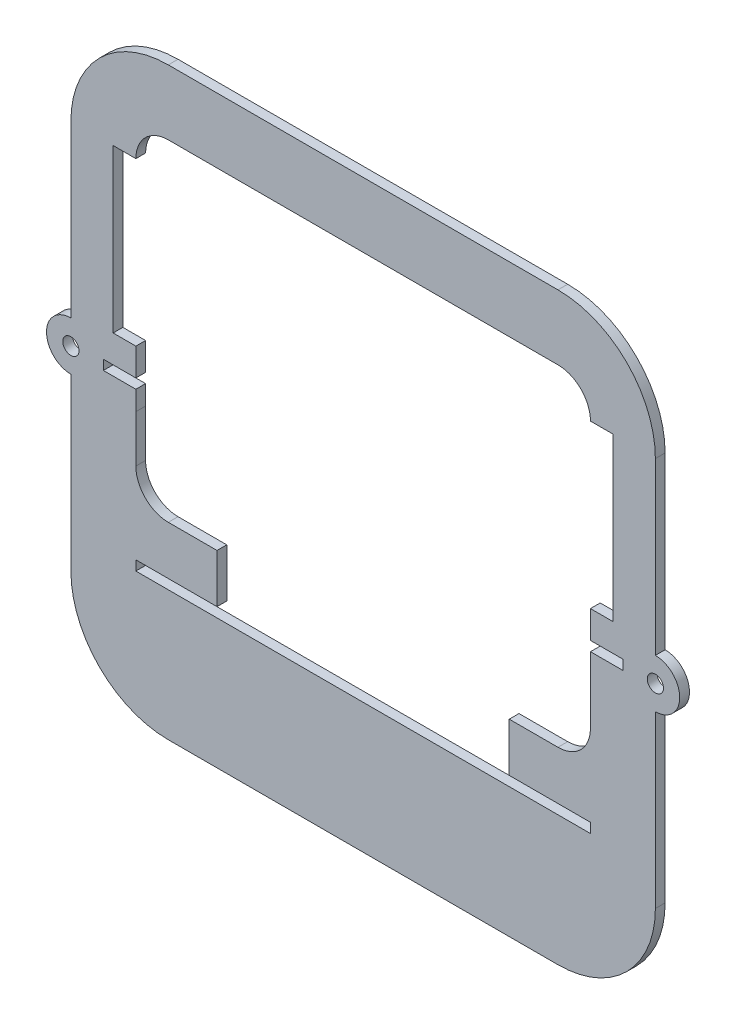
SolidWorks part; units mm, degrees
material "Teak"
ref_plane "Front Plane" through (0, 0, 0) normal (0, 0, 1) x (1, 0, 0)
ref_plane "Top Plane" through (0, 0, 0) normal (0, 1, 0) x (1, 0, 0)
ref_plane "Right Plane" through (0, 0, 0) normal (1, 0, 0) x (0, 0, -1)
sketch "Sketch1" plane through (0, 0, 0) normal (0, 0, 1) x (1, 0, 0)
  line L33 (167.7762, -174.9603) -> (287.7762, -174.9603)
  line L38 (317.7762, -144.9603) -> (317.7762, -92.4603)
  line L41 (226.2847, -14.9603) -> (167.7847, -14.9603)
  line L44 (229.2847, -14.9603) -> (226.2847, -14.9603)
  line L47 (287.7847, -14.9603) -> (229.2847, -14.9603)
  line L48 (304.7847, -24.9603) -> (297.7847, -24.9603)
  line L49 (304.7847, -74.9603) -> (304.7847, -24.9603)
  line L50 (297.7847, -74.9603) -> (304.7847, -74.9603)
  line L51 (297.7847, -83.4603) -> (297.7847, -74.9603)
  line L52 (307.7847, -83.4603) -> (297.7847, -83.4603)
  line L53 (307.7847, -86.4603) -> (307.7847, -83.4603)
  line L54 (297.7847, -86.4603) -> (307.7847, -86.4603)
  line L59 (157.7847, -74.9603) -> (157.7847, -83.4603)
  line L60 (150.7847, -74.9603) -> (157.7847, -74.9603)
  line L61 (150.7847, -24.9603) -> (150.7847, -74.9603)
  line L62 (157.7847, -24.9603) -> (150.7847, -24.9603)
  line L63 (287.7762, 5.0397) -> (167.7762, 5.0397)
  line L64 (137.7762, -24.9603) -> (137.7762, -77.4603)
  line L70 (147.7847, -86.4603) -> (147.7847, -83.4603)
  line L71 (157.7847, -86.4603) -> (147.7847, -86.4603)
  line L72 (147.7847, -83.4603) -> (157.7847, -83.4603)
  line L97 (137.7762, -92.4603) -> (137.7762, -144.9603)
  line L98 (317.7762, -77.4603) -> (317.7762, -24.9603)
  line L109 (297.7762, -134.9603) -> (297.7762, -131.9603)
  line L110 (157.7847, -86.4603) -> (157.7762, -92.4603)
  line L111 (297.7847, -86.4603) -> (297.7762, -92.4603)
  line L112 (157.7762, -134.9603) -> (297.7762, -134.9603)
  line L113 (157.7762, -92.4603) -> (157.7762, -144.9603) construction
  line L114 (167.7762, -154.9603) -> (287.7762, -154.9603) construction
  line L115 (297.7762, -144.9603) -> (297.7762, -92.4603) construction
  line L116 (297.7762, -106.9603) -> (297.7762, -92.4603)
  line L117 (287.7762, -116.9603) -> (272.7762, -116.9603)
  line L119 (297.7762, -131.9603) -> (272.7762, -131.9603)
  line L120 (272.7762, -116.9603) -> (272.7762, -131.9603)
  line L122 (157.7762, -106.9603) -> (157.7762, -92.4603)
  line L123 (157.7762, -134.9603) -> (157.7762, -131.9603)
  line L124 (157.7762, -131.9603) -> (182.7762, -131.9603)
  line L125 (167.7762, -116.9603) -> (182.7762, -116.9603)
  line L126 (182.7762, -116.9603) -> (182.7762, -131.9603)
  arc A22 (167.7847, -14.9603) -> (157.7847, -24.9603) centre (167.7847, -24.9603) ccw
  arc A23 (297.7847, -24.9603) -> (287.7847, -14.9603) centre (287.7847, -24.9603) ccw
  arc A26 (137.7762, -144.9603) -> (167.7762, -174.9603) centre (167.7762, -144.9603) ccw
  arc A27 (287.7762, -174.9603) -> (317.7762, -144.9603) centre (287.7762, -144.9603) ccw
  arc A28 (317.7762, -24.9603) -> (287.7762, 5.0397) centre (287.7762, -24.9603) ccw
  arc A29 (167.7762, 5.0397) -> (137.7762, -24.9603) centre (167.7762, -24.9603) ccw
  circle A50 centre (317.7762, -84.9603) radius 2.5
  arc A51 (317.7762, -92.4603) -> (317.7762, -77.4603) centre (317.7762, -84.9603) ccw
  circle A52 centre (137.7762, -84.9603) radius 2.5
  arc A53 (137.7762, -77.4603) -> (137.7762, -92.4603) centre (137.7762, -84.9603) ccw
  arc A66 (287.7762, -116.9603) -> (297.7762, -106.9603) centre (287.7762, -106.9603) ccw
  arc A67 (167.7762, -116.9603) -> (157.7762, -106.9603) centre (167.7762, -106.9603) cw
  arc A69 (157.7762, -144.9603) -> (167.7762, -154.9603) centre (167.7762, -144.9603) ccw construction
  arc A70 (287.7762, -154.9603) -> (297.7762, -144.9603) centre (287.7762, -144.9603) ccw construction
  dimension "D1" = 15
  dimension "D2" = 5
  dimension "D4" = 15
  dimension "D5" = 5
  dimension "D9" = 10
  dimension "D6" = 3
  dimension "D7" = 15
  dimension "D3" = 20
extrude "Boss-Extrude1" add sketch "Sketch1" along normal blind 3
